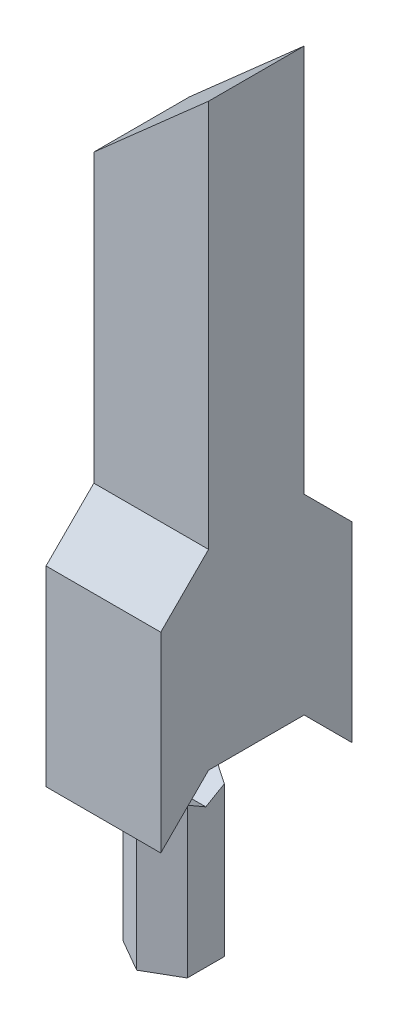
SolidWorks part; units mm, degrees
ref_plane "Front Plane" through (0, 0, 0) normal (0, 0, 1) x (1, 0, 0)
ref_plane "Top Plane" through (0, 0, 0) normal (0, 1, 0) x (1, 0, 0)
ref_plane "Right Plane" through (0, 0, 0) normal (1, 0, 0) x (0, 0, -1)
sketch "Sketch1" plane through (0, 0, 0) normal (0, 1, 0) x (1, 0, 0)
  line L1 (0, -3.875) -> (3.3558, -1.9375)
  line L2 (3.3558, -1.9375) -> (3.3558, 1.9375)
  line L3 (3.3558, 1.9375) -> (0, 3.875)
  line L4 (0, 3.875) -> (-3.3558, 1.9375)
  line L5 (-3.3558, 1.9375) -> (-3.3558, -1.9375)
  line L6 (-3.3558, -1.9375) -> (0, -3.875)
  circle A0 centre (0, 0) radius 3.875 construction
  dimension "D1" = 7.75
extrude "Boss-Extrude1" add sketch "Sketch1" against normal blind 23
sketch "Sketch2" plane through (-3.3558, 0, 0) normal (-1, 0, 0) x (0, 0, 1)
  line L0 (0, 0) -> (0, -5) construction
  circle A0 centre (0, -5) radius 2
  dimension "D2" = 4
  dimension "D1" = 5
extrude "Cut-Extrude1" cut sketch "Sketch2" against normal blind 10
sketch "Sketch3" plane through (3.3558, 0, 0) normal (1, 0, 0) x (0, 0, -1)
  line L1 (0, -8.4641) -> (3, -6.7321)
  line L2 (3, -6.7321) -> (3, -3.2679)
  line L3 (3, -3.2679) -> (0, -1.5359)
  line L4 (0, -1.5359) -> (-3, -3.2679)
  line L5 (-3, -3.2679) -> (-3, -6.7321)
  line L6 (-3, -6.7321) -> (0, -8.4641)
  circle A0 centre (0, -5) radius 3 construction
  dimension "D1" = 6
extrude "Cut-Extrude2" cut sketch "Sketch3" against normal blind 4
sketch "Sketch4" plane through (0, 0, 0) normal (0, 0, 1) x (1, 0, 0)
  line L0 (-3.3558, 0) -> (-3.3558, 50)
  line L1 (-3.3558, 50) -> (8.6442, 60.6066)
  line L2 (8.6442, 60.6066) -> (8.6442, 0)
  line L3 (-3.3558, 0) -> (8.6442, 0)
  dimension "D1" = 50
  dimension "D2" = 12
extrude "Boss-Extrude2" add sketch "Sketch4" along normal mid plane 10
sketch "Sketch5" plane through (-3.3558, 0, 0) normal (-1, 0, 0) x (0, 0, 1)
  line L0 (5, 0) -> (10, -5)
  line L1 (10, -5) -> (10, 15.0033)
  line L2 (10, 15.0033) -> (5, 20.0033)
  line L3 (5, 50) -> (5, 0) construction
  line L4 (5, 20.0033) -> (5, 0)
  line L5 (0, -3.6914) -> (0, 3.6914) construction
  line L6 (-10, 15.0033) -> (-5, 20.0033)
  line L7 (-10, -5) -> (-10, 15.0033)
  line L8 (-5, 0) -> (-10, -5)
  line L9 (-5, 20.0033) -> (-5, 0)
  dimension "D1" = 5
  dimension "D2" = 135
extrude "Boss-Extrude3" add sketch "Sketch5" against normal blind 12
